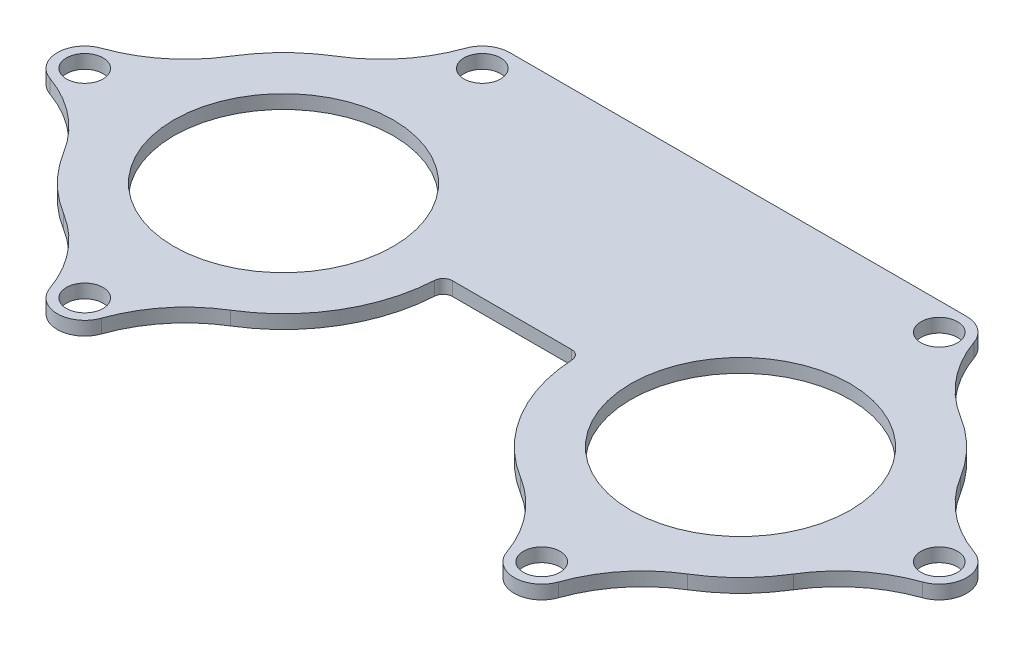
SolidWorks part; units mm, degrees
material "5052-H34"
ref_plane "正面" through (0, 0, 0) normal (0, 0, 1) x (1, 0, 0)
ref_plane "平面" through (0, 0, 0) normal (0, 1, 0) x (1, 0, 0)
ref_plane "右側面" through (0, 0, 0) normal (1, 0, 0) x (0, 0, -1)
sketch "ｽｹｯﾁ1" plane through (0, 0, 0) normal (0, 1, 0) x (1, 0, 0)
  line L0 (0, 0) -> (50, 0) construction
  line L1 (25, 0) -> (25, 30.1421) construction
  line L2 (0, 24.75) -> (50, 24.75)
  line L3 (17.5, 0) -> (32.5, 0)
  circle A0 centre (0, 0) radius 21.75 construction
  circle A1 centre (50, 0) radius 21.75 construction
  circle A2 centre (0, 21.75) radius 2
  circle A3 centre (-21.75, 0) radius 2
  circle A4 centre (0, -21.75) radius 2
  circle A5 centre (50, 21.75) radius 2
  circle A6 centre (71.75, 0) radius 2
  circle A7 centre (50, -21.75) radius 2
  circle A8 centre (0, 0) radius 12
  circle A9 centre (50, 0) radius 12
  circle A11 centre (0, 21.75) radius 3
  circle A12 centre (-21.75, 0) radius 3
  circle A13 centre (0, -21.75) radius 3
  circle A14 centre (50, -21.75) radius 3
  circle A15 centre (71.75, 0) radius 3
  circle A16 centre (50, 21.75) radius 3
  circle A17 centre (0, 0) radius 17.5
  circle A18 centre (50, 0) radius 17.5
  arc A19 (52.8309, 22.7431) -> (59.1459, 14.9199) centre (66.9852, 27.7083) ccw
  arc A20 (72.7431, 2.8309) -> (64.9199, 9.1459) centre (77.7083, 16.9852) cw
  arc A21 (72.7431, -2.8309) -> (64.9199, -9.1459) centre (77.7083, -16.9852) ccw
  arc A22 (59.1459, -14.9199) -> (52.8309, -22.7431) centre (66.9852, -27.7083) ccw
  arc A23 (-9.1459, -14.9199) -> (-2.8309, -22.7431) centre (-16.9852, -27.7083) cw
  arc A24 (-22.7431, -2.8309) -> (-14.9199, -9.1459) centre (-27.7083, -16.9852) cw
  arc A25 (-22.7431, 2.8309) -> (-14.9199, 9.1459) centre (-27.7083, 16.9852) ccw
  arc A26 (-2.8309, 22.7431) -> (-9.1459, 14.9199) centre (-16.9852, 27.7083) cw
  arc A27 (47.1691, -22.7431) -> (40.8541, -14.9199) centre (33.0148, -27.7083) ccw
  arc A28 (2.8309, -22.7431) -> (9.1459, -14.9199) centre (16.9852, -27.7083) cw
  dimension "D2" = 43.5
  dimension "D3" = 4
  dimension "D4" = 24
  dimension "D5" = 6
  dimension "D6" = 35
  dimension "D7" = 15
  dimension "D1" = 50
extrude "ﾎﾞｽ - 押し出し1" add sketch "ｽｹｯﾁ1" along normal blind 1.5 contours A17 A8 | A11 A26 A17 L3 A18 A19 A16 L2 | A11 A2 | A25 A12 A24 A17 | A12 A3 | A13 A28 A17 A23 | A13 A4 | A18 A9 | A21 A15 A20 A18 | A15 A6 | A27 A14 A22 A18 | A14 A7 | A5
fillet "ﾌｨﾚｯﾄ1" radius 1 2 edges at (32.5, 0.75, 0) (17.5, 0.75, 0)
